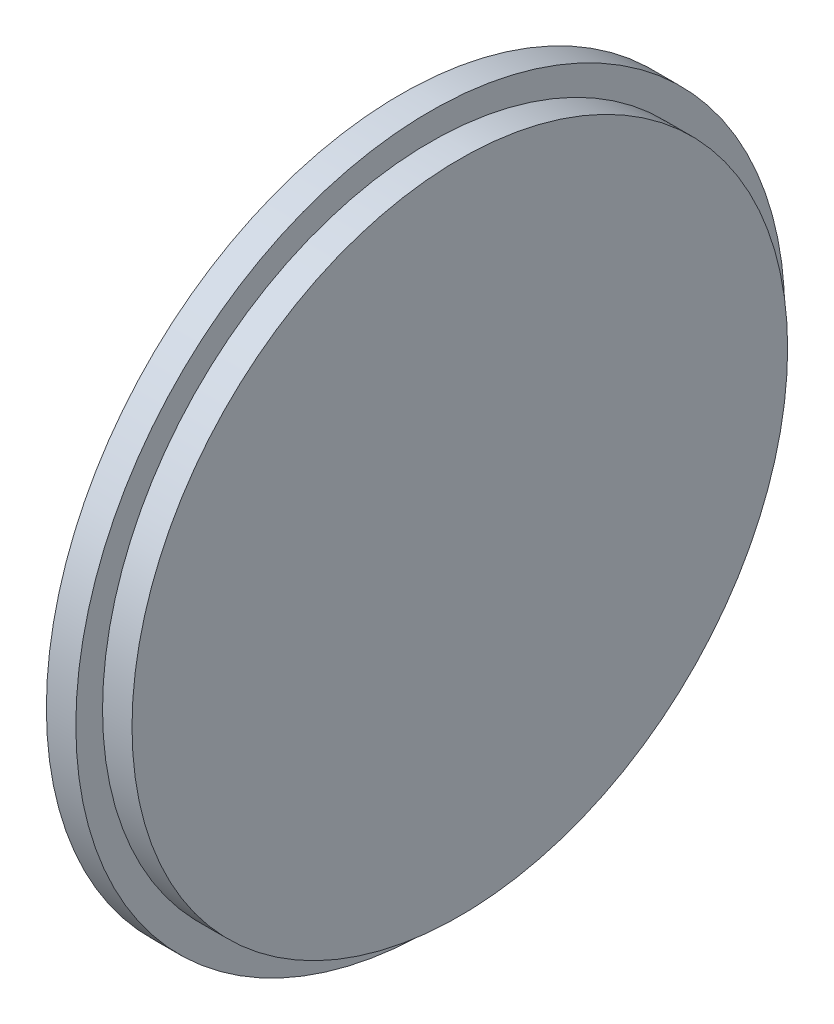
SolidWorks part; units mm, degrees
ref_plane "Front Plane" through (0, 0, 0) normal (0, 0, 1) x (1, 0, 0)
ref_plane "Top Plane" through (0, 0, 0) normal (0, 1, 0) x (1, 0, 0)
ref_plane "Right Plane" through (0, 0, 0) normal (1, 0, 0) x (0, 0, -1)
ref_plane "PX_p26_300" through (26.3, 0, 0) normal (1, 0, 0) x (0, 0, -1)
sketch "S_cyl1" plane through (26.3, 0, 0) normal (1, 0, 0) x (0, 0, -1)
  circle A0 centre (-30, 0) radius 19.25
  dimension "D1_S_cyl1" = 38.5
  dimension "P2" = 30
extrude "Boss_1" add sketch "S_cyl1" along normal blind 1.6
ref_plane "PX_p27_900" through (27.9, 0, 0) normal (1, 0, 0) x (0, 0, -1)
sketch "S_cyl2" plane through (27.9, 0, 0) normal (1, 0, 0) x (0, 0, -1)
  circle A0 centre (-30, 0) radius 17.8
  dimension "D1_S_cyl2" = 35.6
  dimension "P2" = 30
extrude "Boss_2" add sketch "S_cyl2" along normal blind 1.6
equation "\"plate_t\" = 3"
equation "\"clearance\" = 0.4"
